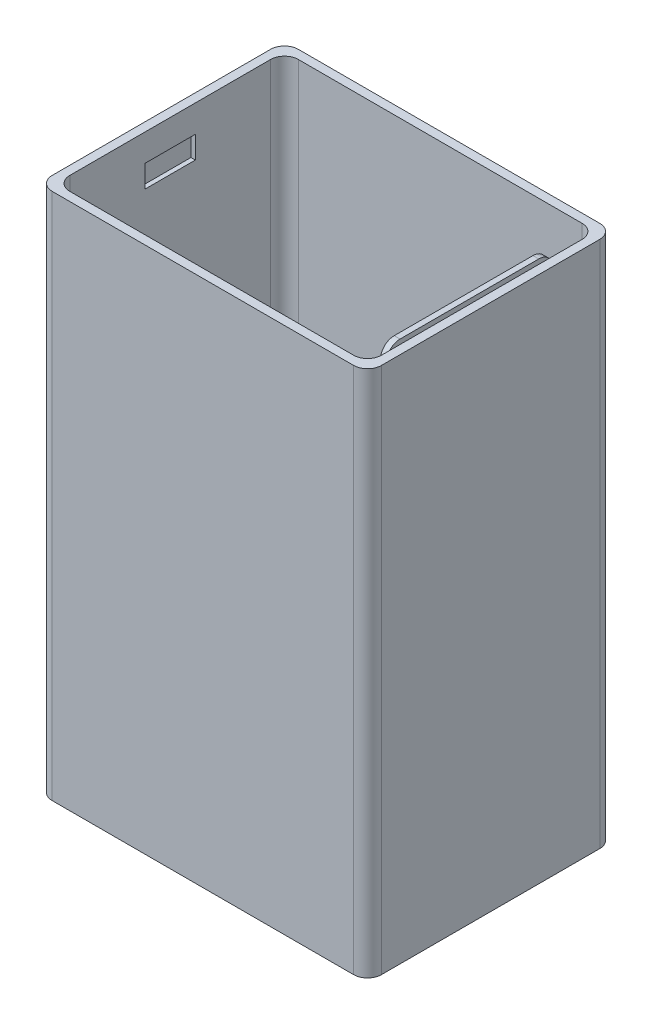
SolidWorks part; units mm, degrees
ref_plane "Front Plane" through (0, 0, 0) normal (0, 0, 1) x (1, 0, 0)
ref_plane "Top Plane" through (0, 0, 0) normal (0, 1, 0) x (1, 0, 0)
ref_plane "Right Plane" through (0, 0, 0) normal (1, 0, 0) x (0, 0, -1)
sketch "Sketch1" plane through (0, 0, 0) normal (0, 1, 0) x (1, 0, 0)
  line L0 (-6.35, 6.35) -> (-6.35, -171.3484)
  line L1 (0, 0) -> (224.9932, 0)
  line L2 (0, 0) -> (0, -164.9984)
  line L3 (0, -164.9984) -> (224.9932, -164.9984)
  line L4 (224.9932, 0) -> (224.9932, -164.9984)
  line L5 (-6.35, -171.3484) -> (231.3432, -171.3484)
  line L6 (231.3432, 6.35) -> (231.3432, -171.3484)
  line L7 (-6.35, 6.35) -> (231.3432, 6.35)
  dimension "D1" = 224.9932
  dimension "D2" = 164.9984
  dimension "D3" = 6.35
extrude "Boss-Extrude1" add sketch "Sketch1" along normal blind 374.65
sketch "Sketch4" plane through (224.9932, 0, 0) normal (-1, 0, 0) x (0, 0, 1)
  line L0 (164.9984, 0) -> (0, 0) construction
  line L1 (28.7274, 0) -> (136.1694, 0)
  line L2 (28.7274, 0) -> (28.7274, 374.65)
  line L3 (28.7274, 374.65) -> (136.1694, 374.65)
  line L4 (136.1694, 0) -> (136.1694, 374.65)
  line L5 (164.9984, 374.65) -> (0, 374.65) construction
  line L8 (164.9984, 374.65) -> (164.9984, 0) construction
  dimension "D1" = 107.442
  dimension "D2" = 28.829
extrude "Boss-Extrude2" add sketch "Sketch4" along normal blind 9.017
sketch "Sketch5" plane through (215.9762, 0, 0) normal (-1, 0, 0) x (0, 0, 1)
  line L0 (136.1694, 374.65) -> (28.7274, 374.65) construction
  line L5 (142.5194, 0) -> (22.3774, 0)
  line L6 (142.5194, 0) -> (142.5194, 374.65)
  line L7 (142.5194, 374.65) -> (22.3774, 374.65)
  line L8 (22.3774, 0) -> (22.3774, 374.65)
  line L9 (28.7274, 0) -> (136.1694, 0) construction
  line L11 (164.9984, 374.65) -> (164.9984, 0) construction
  line L12 (136.1694, 0) -> (136.1694, 374.65) construction
  line L13 (28.7274, 374.65) -> (28.7274, 0) construction
  point P5 (0, 0)
  dimension "D1" = 6.35
  dimension "D2" = 6.35
extrude "Boss-Extrude3" add sketch "Sketch5" along normal blind 4.191
sketch "Sketch7" plane through (0, 374.65, 0) normal (0, 1, 0) x (1, 0, 0)
  line L1 (215.9762, -136.1694) -> (224.9932, -136.1694)
  line L2 (215.9762, -136.1694) -> (215.9762, -28.7274)
  line L3 (215.9762, -28.7274) -> (224.9932, -28.7274)
  line L4 (224.9932, -136.1694) -> (224.9932, -28.7274)
extrude "Cut-Extrude1" cut sketch "Sketch7" against normal blind 21.59
sketch "Sketch10" plane through (0, 374.65, 0) normal (0, 1, 0) x (1, 0, 0)
  line L1 (211.7852, -142.5194) -> (215.9762, -142.5194)
  line L2 (211.7852, -142.5194) -> (211.7852, -22.3774)
  line L3 (211.7852, -22.3774) -> (215.9762, -22.3774)
  line L4 (215.9762, -142.5194) -> (215.9762, -22.3774)
extrude "Cut-Extrude2" cut sketch "Sketch10" against normal blind 5.588
fillet "Fillet1" radius 10 1 edges at (231.3432, 187.325, 171.3484)
fillet "Fillet2" radius 10 1 edges at (224.9932, 187.325, 164.9984)
fillet "Fillet3" radius 10 2 edges at (231.3432, 187.325, -6.35) (224.9932, 187.325, 0)
fillet "Fillet4" radius 10 2 edges at (-6.35, 187.325, 171.3484) (0, 187.325, 164.9984)
fillet "Fillet5" radius 10 2 edges at (0, 187.325, 0) (-6.35, 187.325, -6.35)
fillet "Fillet6" radius 10 2 edges at (220.4847, 353.06, 136.1694) (220.4847, 353.06, 28.7274)
fillet "Fillet7" radius 10 2 edges at (213.8807, 369.062, 22.3774) (213.8807, 369.062, 142.5194)
sketch "Sketch11" plane through (211.7852, 0, 0) normal (-1, 0, 0) x (0, 0, 1)
  line L0 (22.3774, 0) -> (142.5194, 0) construction
  line L1 (57.0484, 0) -> (107.8484, 0)
  line L2 (57.0484, 0) -> (57.0484, 15.24)
  line L3 (57.0484, 15.24) -> (107.8484, 15.24)
  line L4 (107.8484, 0) -> (107.8484, 15.24)
  line L5 (142.5194, 0) -> (142.5194, 359.062) construction
  dimension "D1" = 15.24
  dimension "D2" = 50.8
  dimension "D3" = 34.671
extrude "Boss-Extrude4" add sketch "Sketch11" along normal blind 19.9898
fillet "Fillet10" radius 10 2 edges at (191.7954, 7.62, 107.8484) (191.7954, 7.62, 57.0484)
fillet "Fillet11" radius 10 5 edges at (206.7903, 15.24, 107.8484) (194.7243, 15.24, 104.9195) (206.7903, 15.24, 57.0484) (194.7243, 15.24, 59.9773) (191.7954, 15.24, 82.4484)
sketch "Sketch12" plane through (0, 0, 0) normal (0, -1, 0) x (1, 0, 0)
  line L0 (231.3432, 161.3484) -> (231.3432, 3.65) construction
  line L1 (221.3432, -6.35) -> (3.65, -6.35) construction
  line L2 (-6.35, 3.65) -> (-6.35, 161.3484) construction
  line L3 (3.65, 171.3484) -> (221.3432, 171.3484) construction
  line L4 (231.3432, 161.3484) -> (231.3432, 3.65)
  line L5 (221.3432, -6.35) -> (3.65, -6.35)
  line L6 (-6.35, 3.65) -> (-6.35, 161.3484)
  line L7 (3.65, 171.3484) -> (221.3432, 171.3484)
  arc A0 (231.3432, 161.3484) -> (221.3432, 171.3484) centre (221.3432, 161.3484) ccw construction
  arc A1 (221.3432, -6.35) -> (231.3432, 3.65) centre (221.3432, 3.65) ccw construction
  arc A2 (-6.35, 3.65) -> (3.65, -6.35) centre (3.65, 3.65) ccw construction
  arc A3 (3.65, 171.3484) -> (-6.35, 161.3484) centre (3.65, 161.3484) ccw construction
  arc A4 (231.3432, 161.3484) -> (221.3432, 171.3484) centre (221.3432, 161.3484) ccw
  arc A5 (221.3432, -6.35) -> (231.3432, 3.65) centre (221.3432, 3.65) ccw
  arc A6 (-6.35, 3.65) -> (3.65, -6.35) centre (3.65, 3.65) ccw
  arc A7 (3.65, 171.3484) -> (-6.35, 161.3484) centre (3.65, 161.3484) ccw
extrude "Boss-Extrude5" add sketch "Sketch12" along normal blind 6.35
fillet "Fillet13" radius 10 9 edges at (224.9932, 0, 19.3637) (222.0643, 0, 2.9289) (112.4966, 0, 0) (2.9289, 0, 2.9289) (224.9932, 0, 145.5839) (222.0643, 0, 162.0695) (112.4966, 0, 164.9984) (2.9289, 0, 162.0695) (0, 0, 82.4992)
sketch "Sketch13" plane through (0, 0, 0) normal (1, 0, 0) x (0, 0, -1)
  line L0 (-10, 374.65) -> (-154.9984, 374.65) construction
  line L1 (-100.7542, 355.0412) -> (-64.356, 355.0412)
  line L2 (-100.7542, 355.0412) -> (-100.7542, 338.9122)
  line L3 (-100.7542, 338.9122) -> (-64.356, 338.9122)
  line L4 (-64.356, 355.0412) -> (-64.356, 338.9122)
  line L5 (-10, 10) -> (-10, 374.65) construction
  dimension "D1" = 19.6088
  dimension "D2" = 16.129
  dimension "D3" = 36.3982
  dimension "D4" = 54.356
extrude "Cut-Extrude4" cut sketch "Sketch13" against normal blind 3.175
